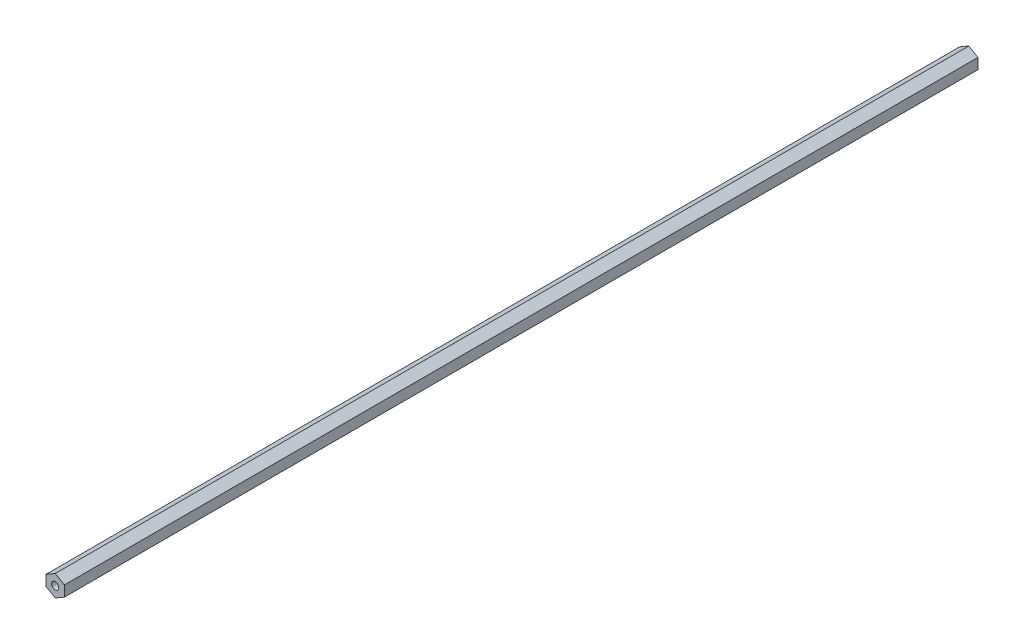
SolidWorks part; units mm, degrees
ref_plane "Front Plane" through (0, 0, 0) normal (0, 0, 1) x (1, 0, 0)
ref_plane "Top Plane" through (0, 0, 0) normal (0, 1, 0) x (1, 0, 0)
ref_plane "Right Plane" through (0, 0, 0) normal (1, 0, 0) x (0, 0, -1)
sketch "Sketch1" plane through (0, 0, 0) normal (0, 0, 1) x (1, 0, 0)
  line L1 (6.35, -3.6662) -> (6.35, 3.6662)
  line L2 (6.35, 3.6662) -> (0, 7.3323)
  line L3 (0, 7.3323) -> (-6.35, 3.6662)
  line L4 (-6.35, 3.6662) -> (-6.35, -3.6662)
  line L5 (-6.35, -3.6662) -> (0, -7.3323)
  line L6 (0, -7.3323) -> (6.35, -3.6662)
  circle A0 centre (0, 0) radius 6.35 construction
  dimension "D1" = 12.7
extrude "Boss-Extrude1" add sketch "Sketch1" along normal mid plane 631.825
sketch "Sketch2" plane through (0, 0, 315.9125) normal (0, 0, 1) x (1, 0, 0)
  circle A0 centre (0, 0) radius 2.4892
  dimension "D1" = 4.9784
extrude "Cut-Extrude1" cut sketch "Sketch2" against normal blind 19.05
mirror "Mirror1" about plane through (0, 0, 0) normal (0, 0, 1) of "Cut-Extrude1"
